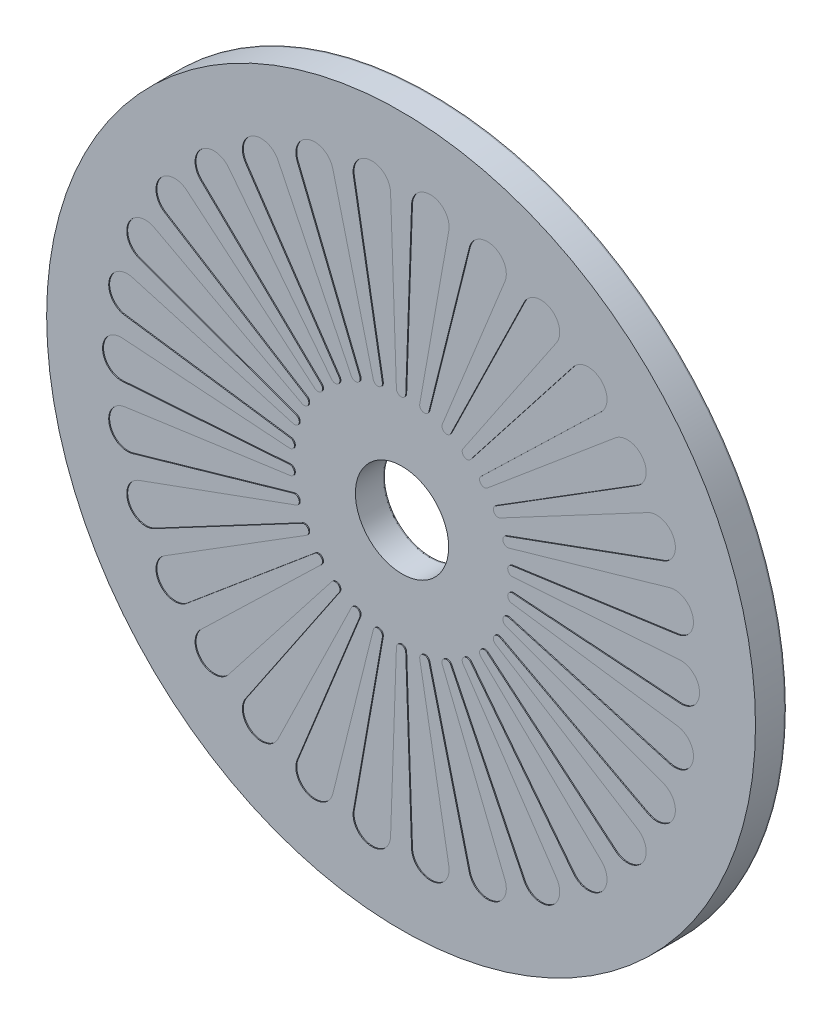
SolidWorks part; units mm, degrees
ref_plane "Front Plane" through (0, 0, 0) normal (0, 0, 1) x (1, 0, 0)
ref_plane "Top Plane" through (0, 0, 0) normal (0, 1, 0) x (1, 0, 0)
ref_plane "Right Plane" through (0, 0, 0) normal (1, 0, 0) x (0, 0, -1)
sketch "Sketch1" plane through (0, 0, 0) normal (0, 0, 1) x (1, 0, 0)
  circle A0 centre (0, 0) radius 38
  circle A1 centre (0, 0) radius 5
  dimension "D1" = 76
  dimension "D2" = 10
extrude "Boss-Extrude1" add sketch "Sketch1" along normal blind 3
sketch "Sketch2" plane through (0, 0, 3) normal (0, 0, 1) x (1, 0, 0)
  line L0 (-1.1256, 29.9067) -> (-0.4997, 11.9826)
  line L1 (0.4997, 11.9826) -> (1.1256, 29.9067)
  line L2 (0, 0) -> (0, -2.3269) construction
  line L4 (0, -2.3269) -> (0, 38) construction
  line L5 (-1.1979, 31.9776) -> (-1.4073, 37.9739) construction
  line L6 (-1.4073, 37.9739) -> (-1.3305, 36.4552) construction
  line L7 (1.4073, 37.9739) -> (1.1979, 31.9776) construction
  line L8 (-6.5986, 37.4227) -> (-5.5567, 31.5138)
  line L9 (6.5986, 37.4227) -> (5.5567, 31.5138)
  line L10 (5.5567, 31.5138) -> (-5.5567, 31.5138) construction
  arc A0 (1.4073, 37.9739) -> (-1.4073, 37.9739) centre (0, 0) ccw
  circle A1 centre (0, 0) radius 38 construction
  arc A2 (-1.4073, 37.9739) -> (-6.5986, 37.4227) centre (0, 0) ccw
  arc A3 (1.4073, 37.9739) -> (6.5986, 37.4227) centre (0, 0) cw
  arc A4 (-5.5567, 31.5138) -> (-3.3327, 31.826) centre (0, 0) cw
  arc A5 (3.3327, 31.826) -> (5.5567, 31.5138) centre (0, 0) cw
  arc A6 (3.3327, 31.826) -> (1.1256, 29.9067) centre (3.1244, 29.8369) ccw
  arc A7 (-3.3327, 31.826) -> (-1.1256, 29.9067) centre (-3.1244, 29.8369) cw
  arc A8 (-0.4997, 11.9826) -> (0.4997, 11.9826) centre (0, 12) ccw
  circle A9 centre (0, 0) radius 5 construction
  dimension "D3" = 6
  dimension "D4" = 2
  dimension "D6" = 0.5
  dimension "D2" = 4
  dimension "D5" = 20
  dimension "11" = 12
extrude "Boss-Extrude2" add sketch "Sketch2" along normal blind 0.1
pattern_circular "CirPattern1" count 30 over 360 about axis through (0, 0, 0) along (0, 0, 1) of "Boss-Extrude2"
sketch "Sketch3" plane through (0, 0, 0) normal (0, 0, -1) x (-1, 0, 0)
  circle A0 centre (0, 0) radius 5
  circle A1 centre (0, 0) radius 38
  circle A2 centre (0, 0) radius 38
  circle A3 centre (0, 0) radius 5 construction
  dimension "D1" = 0
extrude "Boss-Extrude3" add sketch "Sketch3" along normal blind 0.1 separate body
sketch "Sketch5" plane through (0, 0, 0) normal (1, 0, 0) x (0, 0, -1)
  line L0 (-3.1, 0) -> (-19.2509, 0) construction
  line L1 (-3.1, 38) -> (-3.1, -38) construction
  line L2 (0, 38) -> (-3.1, 38) construction
  arc A0 (-19.2509, 0) -> (-3.1, 36.8) centre (30.7491, 0) cw
  dimension "D1" = 50
  dimension "D2" = 1.2
revolve "Revolve-Thin2" [suppressed] add sketch "Sketch5" angle 360 about L0
